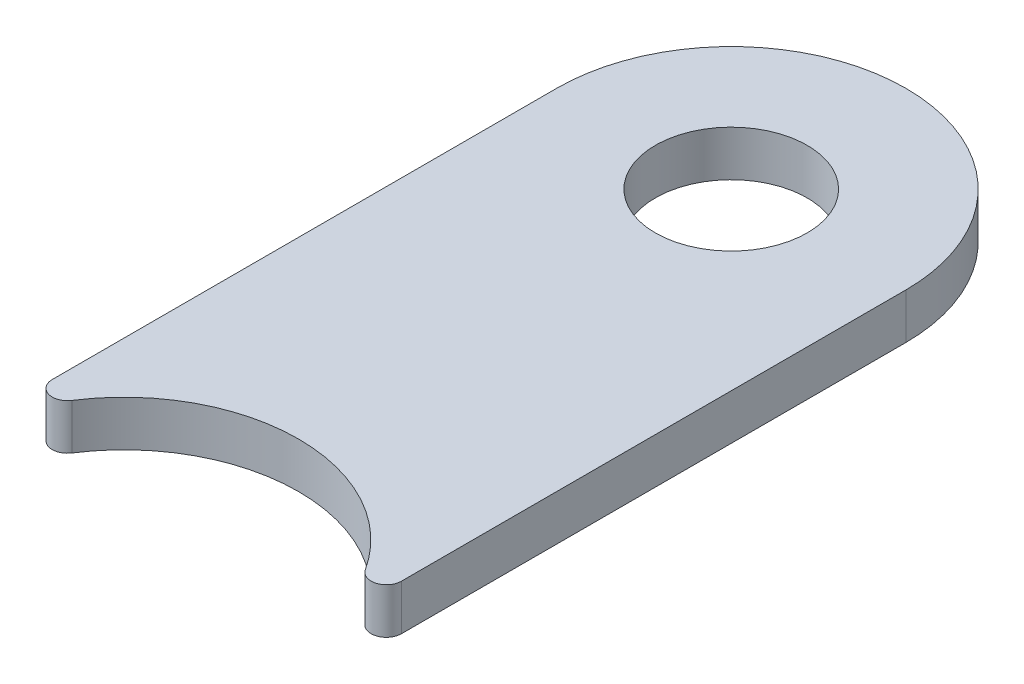
SolidWorks part; units mm, degrees
ref_plane "Front Plane" through (0, 0, 0) normal (0, 0, 1) x (1, 0, 0)
ref_plane "Top Plane" through (0, 0, 0) normal (0, 1, 0) x (1, 0, 0)
ref_plane "Right Plane" through (0, 0, 0) normal (1, 0, 0) x (0, 0, -1)
sketch "Sketch1" plane through (0, 0, 0) normal (0, 1, 0) x (1, 0, 0)
  line L0 (-11.5, 40) -> (-11.5, 0)
  line L1 (11.5, 40) -> (11.5, 0)
  line L2 (-11.5, 0) -> (11.5, 0)
  circle A0 centre (0, 0) radius 11.5
  circle A1 centre (0, 40) radius 11.5
  circle A2 centre (0, 40) radius 5
  dimension "D1" = 10
  dimension "D2" = 23
  dimension "D3" = 40
extrude "Boss-Extrude1" add sketch "Sketch1" along normal blind 3 contours A1 L0 A0 L1 | A1 A2
fillet "Fillet1" radius 1 2 edges at (-11.5, 1.5, 0) (11.5, 1.5, 0)
